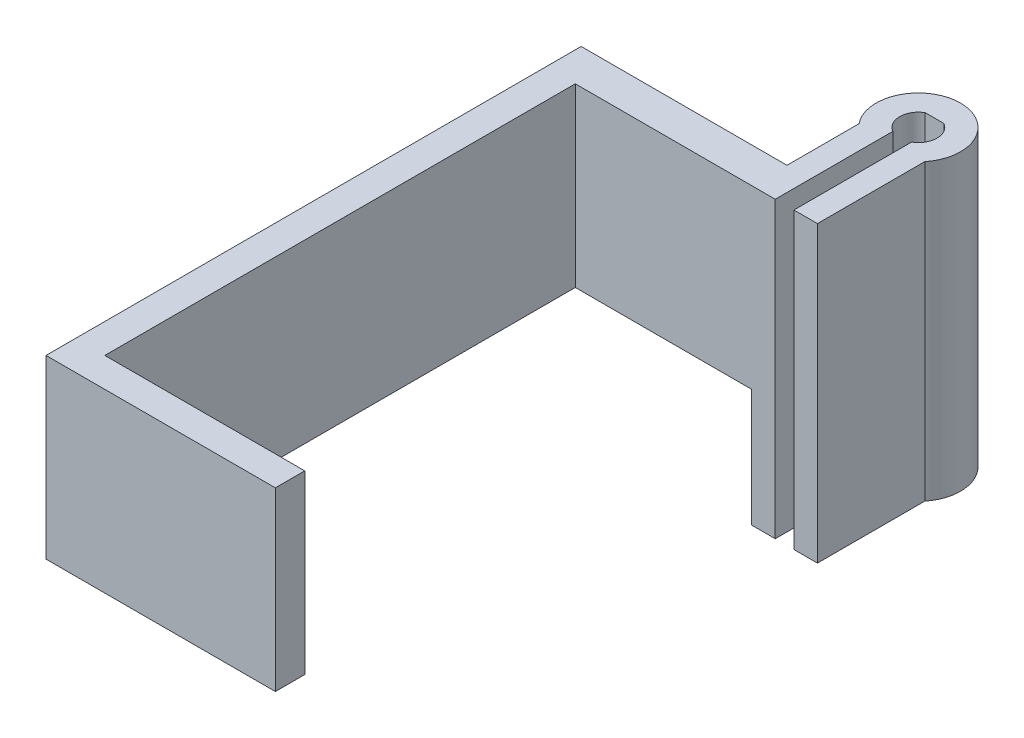
SolidWorks part; units mm, degrees
ref_plane "Front Plane" through (0, 0, 0) normal (0, 0, 1) x (1, 0, 0)
ref_plane "Top Plane" through (0, 0, 0) normal (0, 1, 0) x (1, 0, 0)
ref_plane "Right Plane" through (0, 0, 0) normal (1, 0, 0) x (0, 0, -1)
sketch "Sketch1" plane through (0, 0, 0) normal (0, 1, 0) x (1, 0, 0)
  line L0 (-1.5875, -2.7496) -> (-1.5875, -22.7496)
  line L1 (1.5875, -2.7496) -> (1.5875, -22.7496)
  line L2 (1.5875, 2.7496) -> (-1.5875, 2.7496)
  line L3 (5.5875, -4.5012) -> (5.5875, -22.7496)
  line L4 (-5.5875, -4.5012) -> (-5.5875, -22.7496)
  line L5 (-5.5875, -22.7496) -> (-1.5875, -22.7496)
  line L6 (1.5875, -22.7496) -> (5.5875, -22.7496)
  arc A0 (1.5875, -2.7496) -> (1.5875, 2.7496) centre (0, 0) ccw
  arc A1 (5.5875, -4.5012) -> (-5.5875, -4.5012) centre (0, 0) ccw
  arc A2 (-1.5875, 2.7496) -> (-1.5875, -2.7496) centre (0, 0) ccw
  arc A4 (1.5875, -2.7496) -> (-1.5875, -2.7496) centre (0, 0) ccw construction
  dimension "D1" = 3.175
  dimension "D2" = 20
  dimension "D3" = 3.175
  dimension "D5" = 3.175
  dimension "D4" = 4
extrude "Boss-Extrude1" add sketch "Sketch1" along normal blind 50
sketch "Sketch5" plane through (0, 50, 0) normal (0, 1, 0) x (1, 0, 0)
  line L0 (-5.5875, -22.7496) -> (-35.5875, -22.7496)
  line L1 (-35.5875, -22.7496) -> (-35.5875, -102.7496)
  line L2 (-35.5875, -102.7496) -> (-1.5875, -102.7496)
  line L3 (-1.5875, -102.7496) -> (-1.5875, -107.7496)
  line L4 (-1.5875, -107.7496) -> (-40.5875, -107.7496)
  line L5 (-40.5875, -107.7496) -> (-40.5875, -16.7496)
  line L6 (-40.5875, -16.7496) -> (-5.5875, -16.7496)
  line L7 (-5.5875, -4.5012) -> (-5.5875, -22.7496) construction
  line L8 (-5.5875, -16.7496) -> (-5.5875, -22.7496)
  line L9 (-1.5875, -22.7496) -> (-1.5875, -2.7496) construction
  dimension "D1" = 80
  dimension "D2" = 6
  dimension "D3" = 5
  dimension "D4" = 5
  dimension "D5" = 30
extrude "Boss-Extrude2" add sketch "Sketch5" against normal blind 30
hole_wizard "M4 Clearance Hole1" positions "Sketch2" profile "Sketch3" hole size "M4" standard "ANSI Metric"
sketch "Sketch2" plane through (5.5875, 0, 0) normal (1, 0, 0) x (0, 0, -1)
  line L2 (-22.7496, 50) -> (-22.7496, 0) construction
  line L3 (-22.7496, 0) -> (-4.5012, 0) construction
  line L4 (-22.7496, 50) -> (-4.5012, 50) construction
  point P0 (-15.2496, 40)
  point P4 (-15.2496, 10)
  dimension "D1" = 10
  dimension "D2" = 10
  dimension "D3" = 7.5
sketch "Sketch3" plane through (5.5875, 40, 15.2496) normal (0, 1, 0) x (0, 0, -1)
  line L0 (0, 0) -> (0, 12.7625)
  line L1 (0, 12.7625) -> (2.4, 12.7625)
  line L2 (2.4, 12.7625) -> (2.4, 0)
  line L5 (2.4, 0) -> (0, 0)
  line L11 (0, -6.35) -> (0, 107.95) construction
  dimension "Thru Hole Dia." = 4.8
  dimension "Thru Hole Depth" = 12.7625
ref_plane "Plane1" through (0, 25, 0) normal (0, -1, 0) x (-1, 0, 0)
